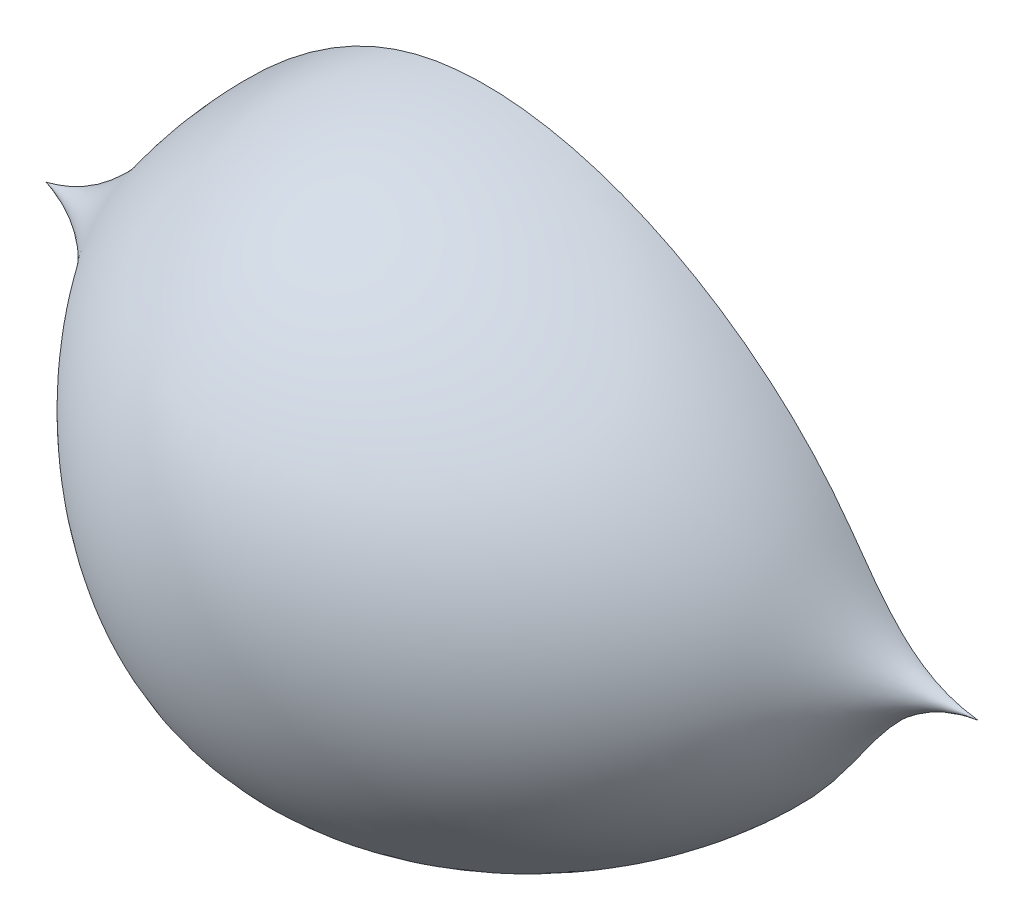
SolidWorks part; units mm, degrees
ref_plane "Front Plane" through (0, 0, 0) normal (0, 0, 1) x (1, 0, 0)
ref_plane "Top Plane" through (0, 0, 0) normal (0, 1, 0) x (1, 0, 0)
ref_plane "Right Plane" through (0, 0, 0) normal (1, 0, 0) x (0, 0, -1)
sketch "Sketch1" plane through (0, 0, 0) normal (0, 0, 1) x (1, 0, 0)
  line L0 (-672.6787, -72.4653) -> (-204.4336, -72.4653)
  spline S0 degree 3 poles (-672.6787, -72.4653) (-638.7999, -63.6234) (-596.0221, 3.8016) (-472.2358, 121.4925) (-287.4292, 33.9577) (-240.9803, -68.1458) (-204.4336, -72.4653) knots 0 0 0 0 0.173486 0.419712 0.829962 1 1 1 1
revolve "Revolve3" add sketch "Sketch1" angle 180 about L0
